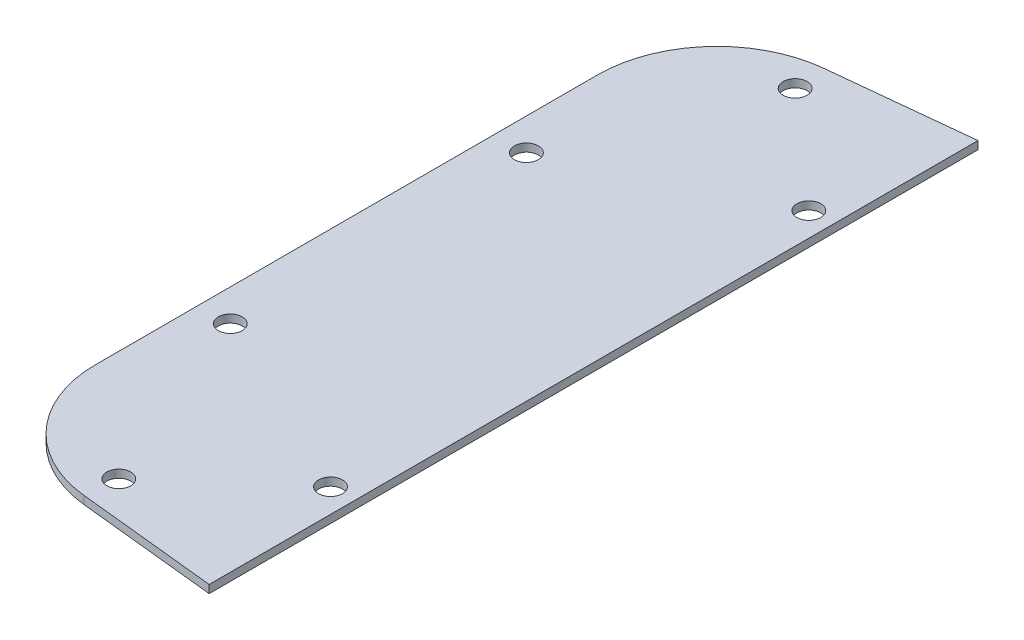
SolidWorks part; units mm, degrees
ref_plane "정면" through (0, 0, 0) normal (0, 0, 1) x (1, 0, 0)
ref_plane "윗면" through (0, 0, 0) normal (0, 1, 0) x (1, 0, 0)
ref_plane "우측면" through (0, 0, 0) normal (1, 0, 0) x (0, 0, -1)
sketch "스케치1" plane through (0, 0, 0) normal (0, 1, 0) x (1, 0, 0)
  line L3 (15.5, 47.3424) -> (-2.051, 45.5177)
  line L4 (-2.051, -47.2786) -> (15.5, -49.1032)
  line L5 (-15.5, 30.5981) -> (-15.5, -32.359)
  line L6 (15.5, 47.3424) -> (15.5, -49.1032)
  arc A2 (-15.5, -32.359) -> (-2.051, -47.2786) centre (-0.5, -32.359) ccw
  arc A3 (-2.051, 45.5177) -> (-15.5, 30.5981) centre (-0.5, 30.5981) ccw
  dimension "D6" = 15
  dimension "D9" = 62.9571
  dimension "D2" = 16
  dimension "D1" = 96.4455
  dimension "D3" = 31
  dimension "D4" = 47.3424
  dimension "D5" = 15.5
  dimension "D7" = 84.065
  dimension "D8" = 84.065
extrude "보스-돌출1" add sketch "스케치1" along normal blind 1
sketch "스케치2" plane through (0, 1, 0) normal (0, 1, 0) x (1, 0, 0)
  line L6 (12.5, -49.1032) -> (12.5, 47.3424)
  line L7 (12.5, -49.1032) -> (12.5, 47.3424) construction
  line L8 (11.5, -44.6658) -> (11.5, 42.905)
  line L9 (11.5, 42.905) -> (-1.6374, 41.5392)
  line L10 (-11.5, 30.5981) -> (-11.5, -32.359)
  line L11 (-1.6374, -43.3) -> (11.5, -44.6658)
  line L13 (11.5, 42.905) -> (-1.6374, 41.5392) construction
  line L14 (-11.5, 30.5981) -> (-11.5, -32.359) construction
  line L15 (-1.6374, -43.3) -> (11.5, -44.6658) construction
  circle A2 centre (-1.6374, 41.5392) radius 1.5
  circle A3 centre (-11.5, 17.695) radius 1.5
  arc A4 (-1.6374, 41.5392) -> (-11.5, 30.5981) centre (-0.5, 30.5981) ccw
  arc A5 (-11.5, -32.359) -> (-1.6374, -43.3) centre (-0.5, -32.359) ccw
  arc A6 (-1.6374, 41.5392) -> (-11.5, 30.5981) centre (-0.5, 30.5981) ccw construction
  arc A7 (-11.5, -32.359) -> (-1.6374, -43.3) centre (-0.5, -32.359) ccw construction
  circle A8 centre (-11.5, -19.4558) radius 1.5
  circle A9 centre (-1.6374, -43.3) radius 1.5
  circle A10 centre (12.5, 29.1196) radius 1.5
  circle A11 centre (12.5, -30.8804) radius 1.5
  point P11 (12.5, -0.8804)
  point P16 (-1.6374, 40.0392)
  point P25 (-1.9457, 41.5027)
  point P26 (11.8372, 42.5793)
  dimension "D2" = 25.21
  dimension "D3" = 25.21
  dimension "D4" = 3
  dimension "D5" = 60
  dimension "D6" = 30
  dimension "D1" = 4
  dimension "D7" = 3
extrude "컷-돌출1" cut sketch "스케치2" against normal up to next
sketch "스케치3" plane through (0, 0, 0) normal (0, -1, 0) x (1, 0, 0)
  line L8 (-11.3, -14.9522) -> (-11.3, 16.7131)
  line L9 (-11.3, 22.1985) -> (-11.3, 32.359)
  line L11 (-1.6168, 43.1011) -> (15.9343, 44.9257)
  line L12 (15.9343, -43.1649) -> (-1.6168, -41.3403)
  line L13 (-11.3, -30.5981) -> (-11.3, 32.359)
  line L14 (1.1113, 43.3847) -> (9.3, 44.236)
  line L15 (9.3, -42.4752) -> (1.1113, -41.6239)
  line L16 (-11.3, -30.5981) -> (-11.3, -20.4377)
  line L18 (9.3, 49.1032) -> (9.3, -47.3424)
  line L19 (9.3, 44.236) -> (9.3, -42.4752)
  arc A0 (-4.263, 42.4822) -> (1.1113, 43.3847) centre (-1.6374, 43.3) ccw
  arc A1 (-11.3, 16.7131) -> (-11.3, 22.1985) centre (-11.5, 19.4558) ccw
  arc A2 (-11.3, -20.4377) -> (-11.3, -14.9522) centre (-11.5, -17.695) ccw
  arc A3 (1.1113, -41.6239) -> (-4.263, -40.7214) centre (-1.6374, -41.5392) ccw
  arc A13 (-1.6168, 43.1011) -> (-11.3, 32.359) centre (-0.5, 32.359) ccw
  arc A14 (-11.3, -30.5981) -> (-1.6168, -41.3403) centre (-0.5, -30.5981) ccw
  arc A15 (-4.263, 42.4822) -> (-11.3, 32.359) centre (-0.5, 32.359) ccw
  arc A16 (-11.3, -30.5981) -> (-4.263, -40.7214) centre (-0.5, -30.5981) ccw
  dimension "D2" = 5.5
  dimension "D1" = 4.2
  dimension "D3" = 6.2
extrude "보스-돌출2" add sketch "스케치3" along normal blind 0.5
